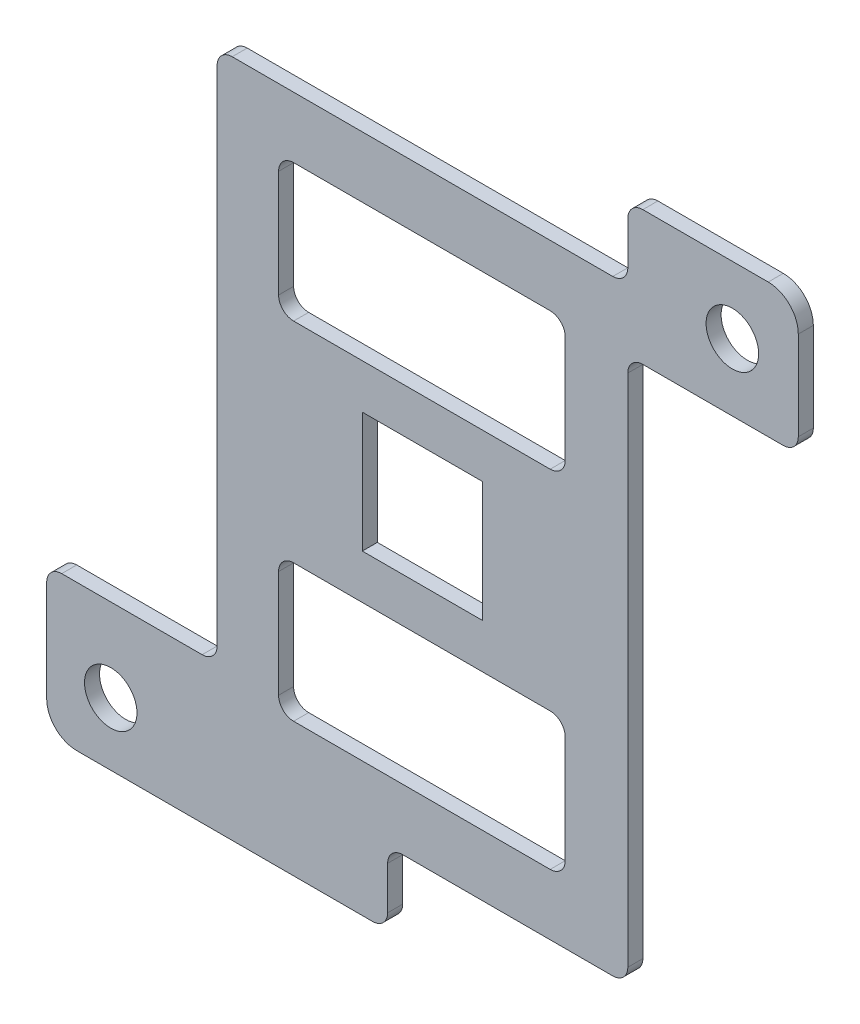
SolidWorks part; units mm, degrees
material "2.0060 (Cu-ETP)"
ref_plane "Plan de face" through (0, 0, 0) normal (0, 0, 1) x (1, 0, 0)
ref_plane "Plan de dessus" through (0, 0, 0) normal (0, 1, 0) x (1, 0, 0)
ref_plane "Plan de droite" through (0, 0, 0) normal (1, 0, 0) x (0, 0, -1)
sketch "Esquisse1" plane through (0, 0, 0) normal (0, 0, 1) x (1, 0, 0)
  line L0 (-100.0535, -75.8656) -> (-118.8871, -75.8656) construction
  line L1 (-105.429, -91.3964) -> (-113.4338, -91.3964)
  line L2 (-105.429, -91.3964) -> (-105.429, -83.3916)
  line L3 (-105.429, -83.3916) -> (-113.4338, -83.3916)
  line L4 (-113.4338, -91.3964) -> (-113.4338, -83.3916)
  line L5 (-105.429, -91.3964) -> (-113.4338, -83.3916) construction
  line L6 (-105.429, -83.3916) -> (-113.4338, -91.3964) construction
  line L9 (-109.4314, -87.394) -> (-99.5695, -87.394) construction
  line L10 (-118.0041, -71.3016) -> (-100.9365, -71.3016)
  line L11 (-119.0041, -72.3016) -> (-119.0041, -79.4296)
  line L12 (-118.0041, -80.4296) -> (-100.9365, -80.4296)
  line L13 (-99.9365, -72.3016) -> (-99.9365, -79.4296)
  line L14 (-119.0041, -71.3016) -> (-99.9365, -80.4296) construction
  line L15 (-119.0041, -80.4296) -> (-99.9365, -71.3016) construction
  line L16 (-118.0041, -103.4864) -> (-100.9365, -103.4864)
  line L17 (-119.0041, -102.4864) -> (-119.0041, -95.3584)
  line L18 (-118.0041, -94.3584) -> (-100.9365, -94.3584)
  line L19 (-99.9365, -102.4864) -> (-99.9365, -95.3584)
  line L21 (-122.0905, -67.2444) -> (-98.0635, -67.2444)
  line L22 (-123.0905, -68.2444) -> (-123.0905, -101.6932)
  line L23 (-110.7497, -107.5436) -> (-96.7723, -107.5436)
  line L24 (-95.7723, -72.3107) -> (-95.7723, -106.5436)
  line L25 (-123.0905, -67.2444) -> (-95.7723, -107.5436) construction
  line L26 (-123.0905, -107.5436) -> (-95.7723, -67.2444) construction
  line L27 (-111.7497, -108.5436) -> (-111.7497, -111.394)
  line L32 (-111.7497, -102.6932) -> (-134.4314, -112.394) construction
  line L33 (-111.7497, -112.394) -> (-134.4314, -102.6932) construction
  line L34 (-124.0905, -102.6932) -> (-133.4314, -102.6932)
  line L35 (-134.4314, -103.6932) -> (-134.4314, -110.394)
  line L36 (-86.4314, -62.394) -> (-94.7723, -62.394)
  line L37 (-84.4314, -64.394) -> (-84.4314, -70.3107)
  line L38 (-85.4314, -71.3107) -> (-94.7723, -71.3107)
  line L40 (-98.0635, -67.2444) -> (-96.7723, -67.2444)
  line L45 (-95.7723, -63.394) -> (-95.7723, -66.2444)
  line L46 (-132.4314, -112.394) -> (-112.7497, -112.394)
  arc A0 (-119.0041, -79.4296) -> (-118.0041, -80.4296) centre (-118.0041, -79.4296) ccw
  arc A1 (-118.0041, -71.3016) -> (-119.0041, -72.3016) centre (-118.0041, -72.3016) ccw
  arc A2 (-100.9365, -71.3016) -> (-99.9365, -72.3016) centre (-100.9365, -72.3016) cw
  arc A3 (-100.9365, -80.4296) -> (-99.9365, -79.4296) centre (-100.9365, -79.4296) ccw
  arc A4 (-100.9365, -103.4864) -> (-99.9365, -102.4864) centre (-100.9365, -102.4864) ccw
  arc A5 (-118.0041, -103.4864) -> (-119.0041, -102.4864) centre (-118.0041, -102.4864) cw
  arc A6 (-119.0041, -95.3584) -> (-118.0041, -94.3584) centre (-118.0041, -95.3584) cw
  arc A7 (-100.9365, -94.3584) -> (-99.9365, -95.3584) centre (-100.9365, -95.3584) cw
  circle A8 centre (-130.1704, -108.2197) radius 1.7457
  arc A9 (-111.7497, -108.5436) -> (-110.7497, -107.5436) centre (-110.7497, -108.5436) cw
  arc A10 (-111.7497, -111.394) -> (-112.7497, -112.394) centre (-112.7497, -111.394) cw
  arc A11 (-124.0905, -102.6932) -> (-123.0905, -101.6932) centre (-124.0905, -101.6932) ccw
  arc A12 (-133.4314, -102.6932) -> (-134.4314, -103.6932) centre (-133.4314, -103.6932) ccw
  arc A14 (-122.0905, -67.2444) -> (-123.0905, -68.2444) centre (-122.0905, -68.2444) ccw
  arc A15 (-96.7723, -107.5436) -> (-95.7723, -106.5436) centre (-96.7723, -106.5436) ccw
  arc A16 (-95.7723, -72.3107) -> (-94.7723, -71.3107) centre (-94.7723, -72.3107) cw
  arc A17 (-84.4314, -70.3107) -> (-85.4314, -71.3107) centre (-85.4314, -70.3107) cw
  arc A18 (-95.7723, -66.2444) -> (-96.7723, -67.2444) centre (-96.7723, -66.2444) cw
  arc A19 (-94.7723, -62.394) -> (-95.7723, -63.394) centre (-94.7723, -63.394) ccw
  arc A20 (-86.4314, -62.394) -> (-84.4314, -64.394) centre (-86.4314, -64.394) cw
  arc A21 (-134.4314, -110.394) -> (-132.4314, -112.394) centre (-132.4314, -110.394) ccw
  circle A22 centre (-88.817, -66.847) radius 1.75
  point P0 (-109.4314, -87.394)
  point P13 (-109.4703, -75.8656)
  point P96 (-84.4314, -62.394)
  dimension "D1" = 1
  dimension "D2" = 1
  dimension "D3" = 1
  dimension "D4" = 2
  dimension "D5" = 2
extrude "Boss.-Extru.1" add sketch "Esquisse1" along normal blind 1
